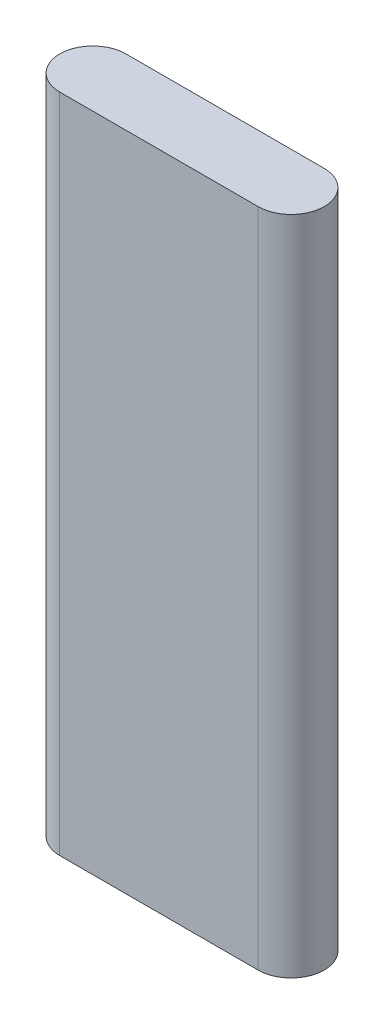
SolidWorks part; units mm, degrees
material "Copper"
ref_plane "Front Plane" through (0, 0, 0) normal (0, 0, 1) x (1, 0, 0)
ref_plane "Top Plane" through (0, 0, 0) normal (0, 1, 0) x (1, 0, 0)
ref_plane "Right Plane" through (0, 0, 0) normal (1, 0, 0) x (0, 0, -1)
sketch "Sketch2" plane through (0, 0, 0) normal (0, 1, 0) x (1, 0, 0)
  line L0 (0, 0) -> (-15, 0)
  line L1 (0, 0) -> (15, 0)
  line L2 (-15, 5) -> (15, 5)
  line L3 (-15, -5) -> (15, -5)
  circle A0 centre (-15, 0) radius 5
  circle A1 centre (15, 0) radius 5
  dimension "D1" = 5
  dimension "D2" = 15
  dimension "D3" = 15
extrude "Boss-Extrude2" add sketch "Sketch2" along normal blind 100
sketch "Sketch3" plane through (0, 0, 0) normal (0, -1, 0) x (-1, 0, 0)
  line L0 (0, 5) -> (0, -5)
  line L1 (15, 5) -> (-15, 5) construction
  line L2 (15, -5) -> (-15, -5) construction
  circle A0 centre (0, 0) radius 2.55
  dimension "D1" = 5.1
extrude "Cut-Extrude1" cut sketch "Sketch3" against normal blind 30 contours L0 A0 | L0 A0
